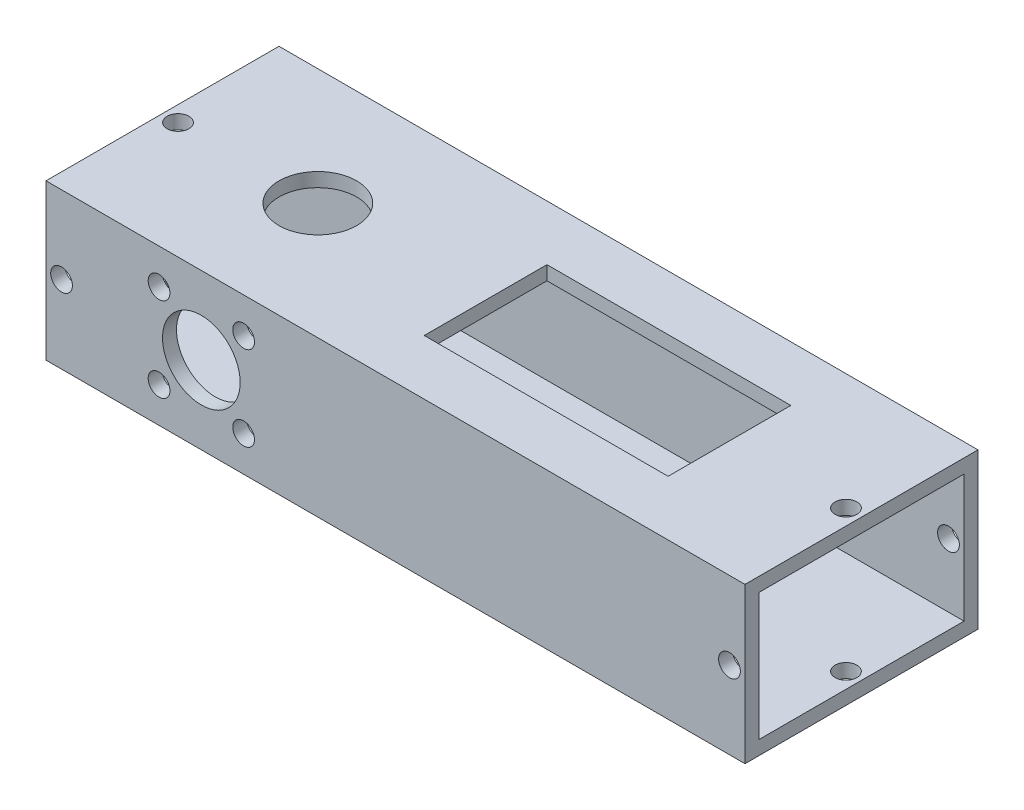
SolidWorks part; units mm, degrees
material "6061-T6 (SS)"
ref_plane "Front Plane" through (0, 0, 0) normal (0, 0, 1) x (1, 0, 0)
ref_plane "Top Plane" through (0, 0, 0) normal (0, 1, 0) x (1, 0, 0)
ref_plane "Right Plane" through (0, 0, 0) normal (1, 0, 0) x (0, 0, -1)
sketch "Sketch1" plane through (0, 0, 0) normal (0, 1, 0) x (1, 0, 0)
  line L1 (0, 0) -> (-114.3, 0)
  line L2 (0, 0) -> (0, -38.1)
  line L3 (0, -38.1) -> (-114.3, -38.1)
  line L4 (-114.3, 0) -> (-114.3, -38.1)
  dimension "D1" = 114.3
  dimension "D2" = 38.1
extrude "Boss-Extrude1" add sketch "Sketch1" along normal blind 25.4
sketch "Sketch2" plane through (0, 0, 0) normal (1, 0, 0) x (0, 0, -1)
  line L0 (0, 0) -> (-2.286, 0) construction
  line L1 (-38.1, 0) -> (0, 0) construction
  line L2 (-2.286, 0) -> (-2.286, 2.286) construction
  line L4 (-2.286, 2.286) -> (-35.814, 2.286)
  line L5 (-2.286, 2.286) -> (-2.286, 23.114)
  line L6 (-2.286, 23.114) -> (-35.814, 23.114)
  line L7 (-35.814, 2.286) -> (-35.814, 23.114)
  dimension "D1" = 20.828
  dimension "D2" = 33.528
extrude "Cut-Extrude1" cut sketch "Sketch2" against normal up to next
sketch "Sketch3" plane through (0, 0, 38.1) normal (0, 0, 1) x (1, 0, 0)
  line L0 (0, 0) -> (0, 12.7) construction
  line L1 (0, 25.4) -> (0, 0) construction
  line L2 (0, 12.7) -> (-2.54, 12.7) construction
  circle A0 centre (-2.54, 12.7) radius 1.778
extrude "Cut-Extrude2" cut sketch "Sketch3" against normal up to next
sketch "Sketch4" plane through (0, 0, 0) normal (0, 0, -1) x (-1, 0, 0)
  line L0 (0, 0) -> (0, 12.7) construction
  line L1 (0, 25.4) -> (0, 0) construction
  line L2 (0, 12.7) -> (2.54, 12.7) construction
  circle A0 centre (2.54, 12.7) radius 1.778
extrude "Cut-Extrude3" cut sketch "Sketch4" against normal up to next
sketch "Sketch5" plane through (0, 0, 38.1) normal (0, 0, 1) x (1, 0, 0)
  line L0 (-114.3, 0) -> (-114.3, 12.7) construction
  line L1 (-114.3, 25.4) -> (-114.3, 0) construction
  line L2 (-114.3, 12.7) -> (-111.76, 12.7) construction
  line L3 (-114.3, 12.7) -> (-88.9, 12.7) construction
  line L4 (-88.9, 12.7) -> (-81.9852, 19.6148) construction
  line L5 (-88.9, 12.7) -> (-95.8148, 5.7852) construction
  line L6 (-88.9, 12.7) -> (-81.9852, 5.7852) construction
  line L7 (-88.9, 12.7) -> (-95.8148, 19.6148) construction
  circle A0 centre (-111.76, 12.7) radius 1.778
  circle A1 centre (-88.9, 12.7) radius 6.35
  circle A2 centre (-95.8148, 19.6148) radius 1.778
  circle A3 centre (-81.9852, 19.6148) radius 1.778
  circle A4 centre (-95.8148, 5.7852) radius 1.778
  circle A5 centre (-81.9852, 5.7852) radius 1.778
  dimension "D1" = 12.7
  dimension "D2" = 3.556
extrude "Cut-Extrude4" cut sketch "Sketch5" against normal up to next
sketch "Sketch6" plane through (0, 0, 0) normal (0, 0, -1) x (-1, 0, 0)
  line L0 (114.3, 0) -> (114.3, 12.7) construction
  line L1 (114.3, 25.4) -> (114.3, 0) construction
  line L2 (114.3, 12.7) -> (111.76, 12.7) construction
  line L3 (114.3, 12.7) -> (88.9, 12.7) construction
  line L4 (88.9, 12.7) -> (81.9852, 5.7852) construction
  line L5 (88.9, 12.7) -> (95.8148, 19.6148) construction
  line L6 (88.9, 12.7) -> (95.8148, 5.7852) construction
  line L7 (88.9, 12.7) -> (81.9852, 19.6148) construction
  circle A0 centre (111.76, 12.7) radius 1.778
  circle A1 centre (88.9, 12.7) radius 6.35
  circle A2 centre (81.9852, 19.6148) radius 1.778
  circle A3 centre (95.8148, 19.6148) radius 1.778
  circle A4 centre (95.8148, 5.7852) radius 1.778
  circle A5 centre (81.9852, 5.7852) radius 1.778
  dimension "D1" = 12.7
extrude "Cut-Extrude5" cut sketch "Sketch6" against normal up to next
sketch "Sketch7" plane through (0, 25.4, 0) normal (0, 1, 0) x (1, 0, 0)
  line L0 (-114.3, -38.1) -> (-114.3, -19.05) construction
  line L1 (-114.3, 0) -> (-114.3, -38.1) construction
  line L2 (-114.3, -19.05) -> (-111.76, -19.05) construction
  line L3 (-114.3, -19.05) -> (-88.9, -19.05) construction
  line L4 (-88.9, -19.05) -> (-61.468, -19.05) construction
  line L5 (-61.468, -19.05) -> (-61.468, -9.017)
  line L6 (-61.468, -19.05) -> (-61.468, -29.083)
  line L7 (-61.468, -29.083) -> (-21.59, -29.083)
  line L8 (-61.468, -9.017) -> (-21.59, -9.017)
  line L9 (-21.59, -29.083) -> (-21.59, -9.017)
  circle A0 centre (-111.76, -19.05) radius 1.778
  circle A1 centre (-88.9, -19.05) radius 6.35
  dimension "D1" = 12.7
extrude "Cut-Extrude6" cut sketch "Sketch7" against normal up to next
sketch "Sketch8" plane through (0, 0, 0) normal (0, -1, 0) x (1, 0, 0)
  line L0 (-114.3, 38.1) -> (-114.3, 19.05) construction
  line L1 (-114.3, 0) -> (-114.3, 38.1) construction
  line L2 (-114.3, 19.05) -> (-111.76, 19.05) construction
  line L3 (-114.3, 19.05) -> (-88.9, 19.05) construction
  line L4 (-88.9, 19.05) -> (-61.468, 19.05) construction
  line L5 (-61.468, 19.05) -> (-61.468, 29.083)
  line L6 (-61.468, 19.05) -> (-61.468, 9.017)
  line L8 (-61.468, 9.017) -> (-21.59, 9.017)
  line L9 (-61.468, 29.083) -> (-21.59, 29.083)
  line L10 (-21.59, 29.083) -> (-21.59, 9.017)
  circle A0 centre (-111.76, 19.05) radius 1.778
  circle A1 centre (-88.9, 19.05) radius 6.35
  dimension "D1" = 12.7
extrude "Cut-Extrude7" cut sketch "Sketch8" against normal up to next
sketch "Sketch9" plane through (0, 25.4, 0) normal (0, 1, 0) x (1, 0, 0)
  line L0 (0, -38.1) -> (0, -19.05) construction
  line L1 (0, -38.1) -> (0, 0) construction
  line L2 (0, -19.05) -> (-2.54, -19.05) construction
  circle A0 centre (-2.54, -19.05) radius 1.778
extrude "Cut-Extrude8" cut sketch "Sketch9" against normal up to next
sketch "Sketch10" plane through (0, 0, 0) normal (0, -1, 0) x (-1, 0, 0)
  line L0 (0, -38.1) -> (0, -19.05) construction
  line L1 (0, -38.1) -> (0, 0) construction
  line L2 (0, -19.05) -> (2.54, -19.05) construction
  circle A0 centre (2.54, -19.05) radius 1.778
extrude "Cut-Extrude9" cut sketch "Sketch10" against normal up to next
